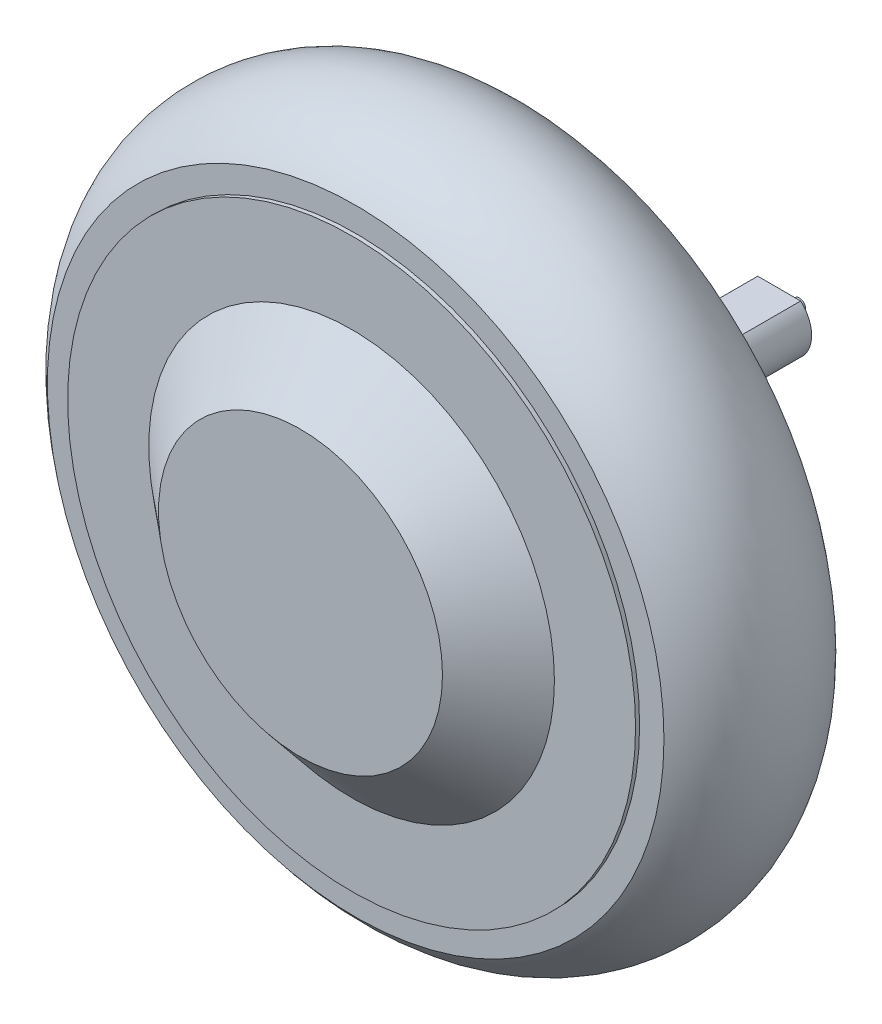
SolidWorks part; units mm, degrees
ref_plane "前视基准面" through (0, 0, 0) normal (0, 0, 1) x (1, 0, 0)
ref_plane "上视基准面" through (0, 0, 0) normal (0, 1, 0) x (1, 0, 0)
ref_plane "右视基准面" through (0, 0, 0) normal (1, 0, 0) x (0, 0, -1)
sketch "草图1" plane through (0, 0, 0) normal (1, 0, 0) x (0, 0, -1)
  line L0 (0, 0) -> (154966.3609, 0) construction
  line L1 (-34.6, 0) -> (-34.6, 35)
  line L2 (-34.6, 35) -> (-22, 50)
  line L3 (0, 0) -> (0, -154966.3609) construction
  line L4 (-22, 50) -> (-22, 70)
  line L5 (-22, 70) -> (-21, 70)
  line L6 (-21, 70) -> (-21, 76)
  line L7 (-1.7245, 86.5) -> (49998.2755, 86.5) construction
  line L8 (21, 70) -> (21, 76)
  line L9 (22, 70) -> (21, 70)
  line L10 (22, 50) -> (22, 70)
  line L11 (34.6, 35) -> (22, 50)
  line L12 (34.6, 25) -> (34.6, 35)
  line L13 (34.6, 25) -> (40.4, 19.2)
  line L14 (40.4, 19.2) -> (40.4, 12)
  line L15 (40.4, 12) -> (45.4, 12)
  line L16 (45.4, 12) -> (45.4, 14)
  line L17 (45.4, 14) -> (48.4, 14)
  line L18 (48.4, 14) -> (48.4, 16)
  line L19 (48.4, 16) -> (50.4, 16)
  line L20 (50.4, 16) -> (50.4, 8)
  line L21 (50.4, 8) -> (83.4, 8)
  line L22 (83.4, 1.5) -> (83.4, 8)
  line L23 (83.4, 1.5) -> (88.4, 1.5)
  line L24 (88.4, 1.5) -> (88.4, 0)
  line L25 (-34.6, 0) -> (88.4, 0)
  arc A0 (-21, 76) -> (21, 76) centre (0, 60.25) cw
  dimension "D4" = 86.5
  dimension "D9" = 43
  dimension "D1" = 34.6
  dimension "D2" = 44
  dimension "D3" = 1
  dimension "D5" = 50
  dimension "D6" = 35
  dimension "D7" = 6
  dimension "D8" = 20
  dimension "D10" = 5
  dimension "D11" = 16
  dimension "D12" = 24
  dimension "D13" = 14
  dimension "D14" = 16
  dimension "D15" = 5.8
  dimension "D16" = 45
  dimension "D17" = 25
  dimension "D18" = 3
  dimension "D19" = 5
  dimension "D20" = 2
  dimension "D21" = 3
revolve "旋转1" add sketch "草图1" angle 360 about L0
sketch "草图2" plane through (0, 0, -83.4) normal (0, 0, -1) x (-1, 0, 0)
  line L0 (-5.2915, 6) -> (5.2915, 6)
  line L1 (-5.2915, -6) -> (5.2915, -6)
  circle A0 centre (0, 0) radius 8 construction
  arc A1 (5.2915, 6) -> (-5.2915, 6) centre (0, 0) ccw
  arc A2 (-5.2915, -6) -> (5.2915, -6) centre (0, 0) ccw
  dimension "D1" = 12
  dimension "D2" = 6
extrude "切除-拉伸1" cut sketch "草图2" against normal up to surface (33 mm away) and the other way through all up to face at (16, 0, -50.4)
